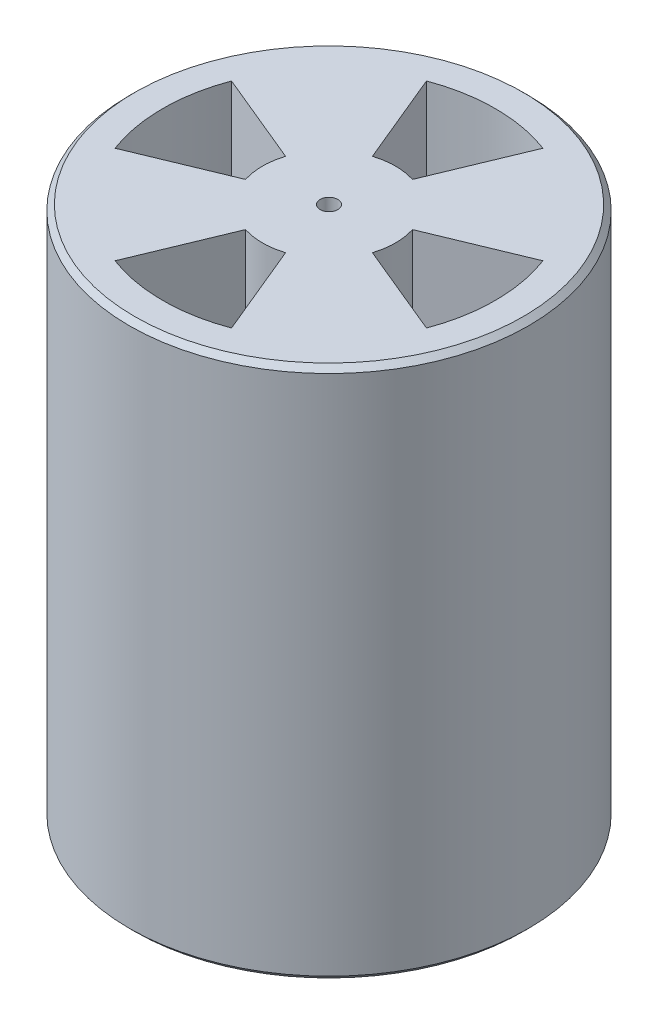
SolidWorks part; units mm, degrees
ref_plane "Front Plane" through (0, 0, 0) normal (0, 0, 1) x (1, 0, 0)
ref_plane "Top Plane" through (0, 0, 0) normal (0, 1, 0) x (1, 0, 0)
ref_plane "Right Plane" through (0, 0, 0) normal (1, 0, 0) x (0, 0, -1)
sketch "Sketch1" plane through (0, 0, 0) normal (0, 1, 0) x (1, 0, 0)
  circle A0 centre (0, 0) radius 76.1365
  dimension "D1" = 152.273
extrude "Boss-Extrude1" add sketch "Sketch1" along normal blind 203.2
chamfer "Chamfer1" distance 2.032 angle 45 2 edges at (0, 0, 76.1365) (0, 203.2, 76.1365)
sketch "Sketch2" plane through (0, 203.2, 0) normal (0, 1, 0) x (1, 0, 0)
  line L0 (-12.7, 0) -> (0, 0) construction
  line L1 (0, 0) -> (12.7, 0) construction
  circle A0 centre (0, 0) radius 25.4 construction
  circle A1 centre (-12.7, 0) radius 3.175
  circle A2 centre (12.7, 0) radius 3.175
  dimension "D1" = 6.35
  dimension "D2" = 50.8
  dimension "D3" = 12.7
  dimension "D4" = 12.7
extrude "Cut-Extrude1" [suppressed] cut sketch "Sketch2" against normal through all both and the other way through all
sketch "Sketch3" plane through (0, 203.2, 0) normal (0, 1, 0) x (1, 0, 0)
  line L0 (0, 25.4) -> (0, 63.4365) construction
  line L1 (-7.6471, 24.2215) -> (-22.225, 59.4158)
  line L2 (7.6471, 24.2215) -> (22.225, 59.4158)
  line L11 (24.2215, 7.6471) -> (59.4158, 22.225)
  line L12 (24.2215, -7.6471) -> (59.4158, -22.225)
  line L13 (7.6471, -24.2215) -> (22.225, -59.4158)
  line L14 (-7.6471, -24.2215) -> (-22.225, -59.4158)
  line L15 (-24.2215, -7.6471) -> (-59.4158, -22.225)
  line L16 (-24.2215, 7.6471) -> (-59.4158, 22.225)
  arc A0 (7.6471, 24.2215) -> (-7.6471, 24.2215) centre (0, 0) ccw
  arc A1 (22.225, 59.4158) -> (-22.225, 59.4158) centre (0, 0) ccw
  circle A2 centre (0, 0) radius 76.1365 construction
  arc A3 (-7.6471, 24.2215) -> (7.6471, 24.2215) centre (0, 0) ccw construction
  arc A4 (-22.225, 59.4158) -> (22.225, 59.4158) centre (0, 0) ccw construction
  arc A13 (24.2215, -7.6471) -> (24.2215, 7.6471) centre (0, 0) ccw
  arc A14 (59.4158, -22.225) -> (59.4158, 22.225) centre (0, 0) ccw
  arc A15 (-7.6471, -24.2215) -> (7.6471, -24.2215) centre (0, 0) ccw
  arc A16 (-22.225, -59.4158) -> (22.225, -59.4158) centre (0, 0) ccw
  arc A17 (-24.2215, 7.6471) -> (-24.2215, -7.6471) centre (0, 0) ccw
  arc A18 (-59.4158, 22.225) -> (-59.4158, -22.225) centre (0, 0) ccw
  point P24 (0, 0)
  point P28 (0, 0)
  dimension "D1" = 12.7
  dimension "D2" = 50.8
  dimension "D3" = 45
  dimension "D4" = 22.5
  dimension "D5" = 22.225
  dimension "D6" = 22.225
  dimension "D7" = 4
extrude "Cut-Extrude2" cut sketch "Sketch3" against normal through all both and the other way through all
sketch "Sketch4" plane through (0, 203.2, 0) normal (0, 1, 0) x (1, 0, 0)
  point P0 (0, 0)
hole_wizard "1/4 Clearance Hole1" positions "Sketch4" profile "Sketch5" hole size "1/4" standard "ANSI Inch" end condition through all
sketch "Sketch5" plane through (0, 203.2, 0) normal (1, 0, 0) x (0, 0, 1)
  line L0 (0, 0) -> (0, 203.2)
  line L1 (0, 203.2) -> (3.3782, 203.2)
  line L2 (3.3782, 203.2) -> (3.3782, 0)
  line L5 (3.3782, 0) -> (0, 0)
  line L11 (0, -6.35) -> (0, 107.95) construction
  dimension "Thru Hole Dia." = 6.7564
  dimension "Thru Hole Depth" = 203.2
sketch "Sketch6" plane through (0, 0, 0) normal (0, -1, 0) x (1, 0, 0)
  circle A0 centre (0, 0) radius 15.875
  dimension "D1" = 31.75
extrude "Cut-Extrude3" cut sketch "Sketch6" against normal blind 15.875
chamfer "Chamfer2" distance 2.54 angle 45 1 edges at (0, 0, -15.875)
equation "\"OD\"= 6"
equation "\"offset\"= 0.005"
equation "\"L\"= 8"
equation "\"D1@Sketch1\"=\"OD\"-\"offset\""
equation "\"D1@Boss-Extrude1\"=\"L\""
